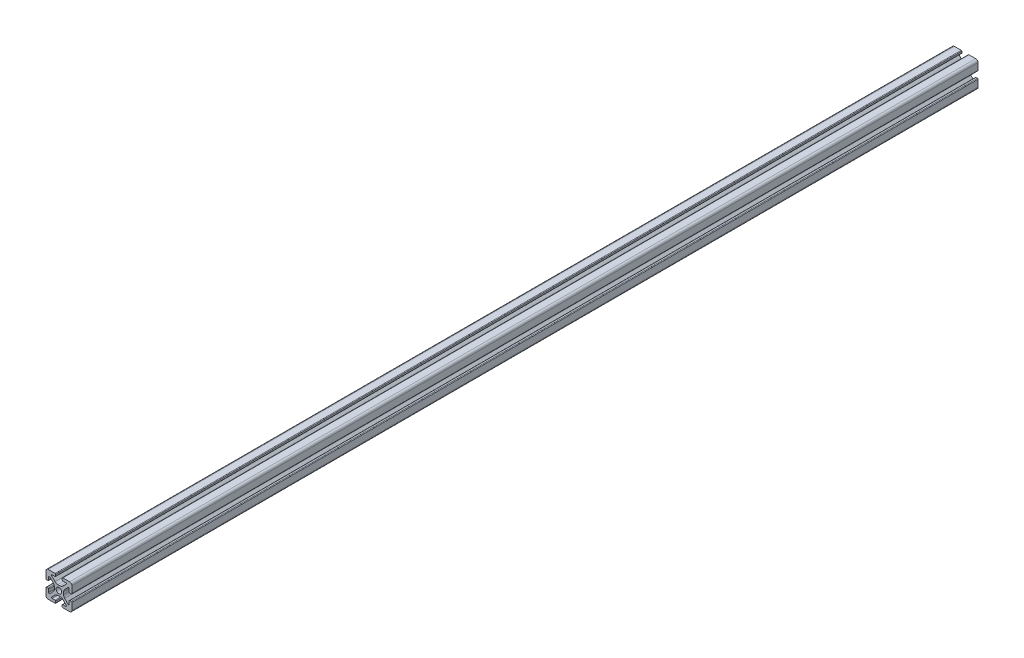
SolidWorks part; units mm, degrees
ref_plane "Front Plane" through (0, 0, 0) normal (0, 0, 1) x (1, 0, 0)
ref_plane "Top Plane" through (0, 0, 0) normal (0, 1, 0) x (1, 0, 0)
ref_plane "Right Plane" through (0, 0, 0) normal (1, 0, 0) x (0, 0, -1)
sketch "Sketch2" plane through (0, 0, 0) normal (0, 0, 1) x (1, 0, 0)
  line L0 (0, 10) -> (0, -10) construction
  line L1 (-10, 0) -> (10, 0) construction
  line L2 (2.5, -10) -> (10, -10)
  line L3 (10, -10) -> (10, -2.5)
  line L4 (2.5, -10) -> (2.5, -7.9246)
  line L5 (2.5, -7.9246) -> (6.4571, -7.9246)
  line L6 (6.4571, -7.9246) -> (2.1325, -3.6)
  line L7 (0, 0) -> (10, -10) construction
  line L8 (10, -2.5) -> (7.9246, -2.5)
  line L9 (7.9246, -2.5) -> (7.9246, -6.4571)
  line L10 (7.9246, -6.4571) -> (3.6, -2.1325)
  line L11 (5.7623, -4.2948) -> (4.2948, -5.7623) construction
  circle A0 centre (0, 0) radius 2.15
  arc A1 (5.25, -7.9246) -> (5.6036, -7.0711) centre (5.25, -7.4246) ccw construction
  point P8 (0, -3.6)
  point P16 (5.0286, -5.0286)
  dimension "Center Hole Diameter" = 4.3
  dimension "D3" = 0.5
  dimension "Rail Height" = 20
  dimension "Rail Width" = 20
  dimension "T-Slot Width" = 5
  dimension "Slot Depth" = 6.4
  dimension "Slot Inner Width" = 11.5
sketch "Sketch3" plane through (0, 0, 0) normal (1, 0, 0) x (0, 0, -1)
  line L0 (-457.2, -10) -> (457.2, -10) construction
  line L1 (-431.8, 0) -> (431.8, 0) construction
  line L2 (0, 10) -> (0, -10) construction
  line L3 (0, 10) -> (0, -10) construction
  point P6 (-431.8, 0)
  point P8 (431.8, 0)
  dimension "Length" = 914.4
  dimension "D1" = 25.4
sketch "Sketch4" plane through (0, 0, 0) normal (0, 0, 1) x (1, 0, 0)
  line L0 (3, -10) -> (8.25, -10)
  line L1 (2.5, -10) -> (10, -10) construction
  line L2 (2.5, -10) -> (2.5, -7.9246) construction
  line L3 (2.5, -7.9246) -> (6.4571, -7.9246) construction
  line L4 (2.5, -8.4246) -> (2.5, -9.5)
  line L5 (3, -7.9246) -> (5.25, -7.9246)
  line L6 (0, -3.6) -> (0.8898, -3.6)
  line L7 (6.4571, -7.9246) -> (2.1325, -3.6) construction
  line L8 (3.0112, -4.4787) -> (5.6036, -7.0711)
  line L9 (10, -10) -> (10, -2.5) construction
  line L10 (7.9246, -6.4571) -> (3.6, -2.1325) construction
  line L11 (7.9246, -2.5) -> (7.9246, -6.4571) construction
  line L12 (7.9246, -5.25) -> (7.9246, -3)
  line L13 (10, -2.5) -> (7.9246, -2.5) construction
  line L14 (8.4246, -2.5) -> (9.5, -2.5)
  line L15 (10, -3) -> (10, -8.25)
  line L16 (7.0711, -5.6036) -> (4.4787, -3.0112)
  line L17 (3.6, 0) -> (3.6, -0.8898)
  line L18 (-10, 0) -> (10, 0) construction
  line L19 (0, -3.6) -> (0, -2.15)
  line L20 (0, 10) -> (0, -10) construction
  line L21 (3.6, 0) -> (2.15, 0)
  arc A0 (2.5, -9.5) -> (3, -10) centre (3, -9.5) ccw
  arc A1 (5.25, -7.9246) -> (5.6036, -7.0711) centre (5.25, -7.4246) ccw construction
  arc A2 (2.5, -8.4246) -> (3, -7.9246) centre (3, -8.4246) cw
  arc A3 (5.25, -7.9246) -> (5.6036, -7.0711) centre (5.25, -7.4246) ccw
  arc A4 (0.8898, -3.6) -> (3.0112, -4.4787) centre (0.8898, -6.6) cw
  arc A5 (8.25, -10) -> (10, -8.25) centre (8.25, -8.25) ccw
  arc A6 (7.0711, -5.6036) -> (7.9246, -5.25) centre (7.4246, -5.25) ccw
  arc A7 (7.9246, -3) -> (8.4246, -2.5) centre (8.4246, -3) cw
  arc A8 (9.5, -2.5) -> (10, -3) centre (9.5, -3) cw
  arc A9 (4.4787, -3.0112) -> (3.6, -0.8898) centre (6.6, -0.8898) cw
  circle A10 centre (0, 0) radius 2.15 construction
  arc A11 (0, -2.15) -> (2.15, 0) centre (0, 0) ccw
  dimension "D1" = 1.75
  dimension "D2" = 3
extrude "Boss-Extrude1" add sketch "Sketch4" along normal mid plane 700
mirror "Mirror1" about plane through (0, 0, 0) normal (1, 0, 0) of bodies 134
mirror "Mirror2" about plane through (0, 0, 0) normal (0, 1, 0) of bodies 135
equation "\"D3@Sketch2\"=\"T-Slot Width@Sketch2\"*0.1"
equation "\"D1@Sketch4\"=\"D3@Sketch2\"*3.5"
equation "\"D2@Sketch4\"=\"D3@Sketch2\"*6"
equation "\"D1@Boss-Extrude1\"=\"Length@Sketch3\""
